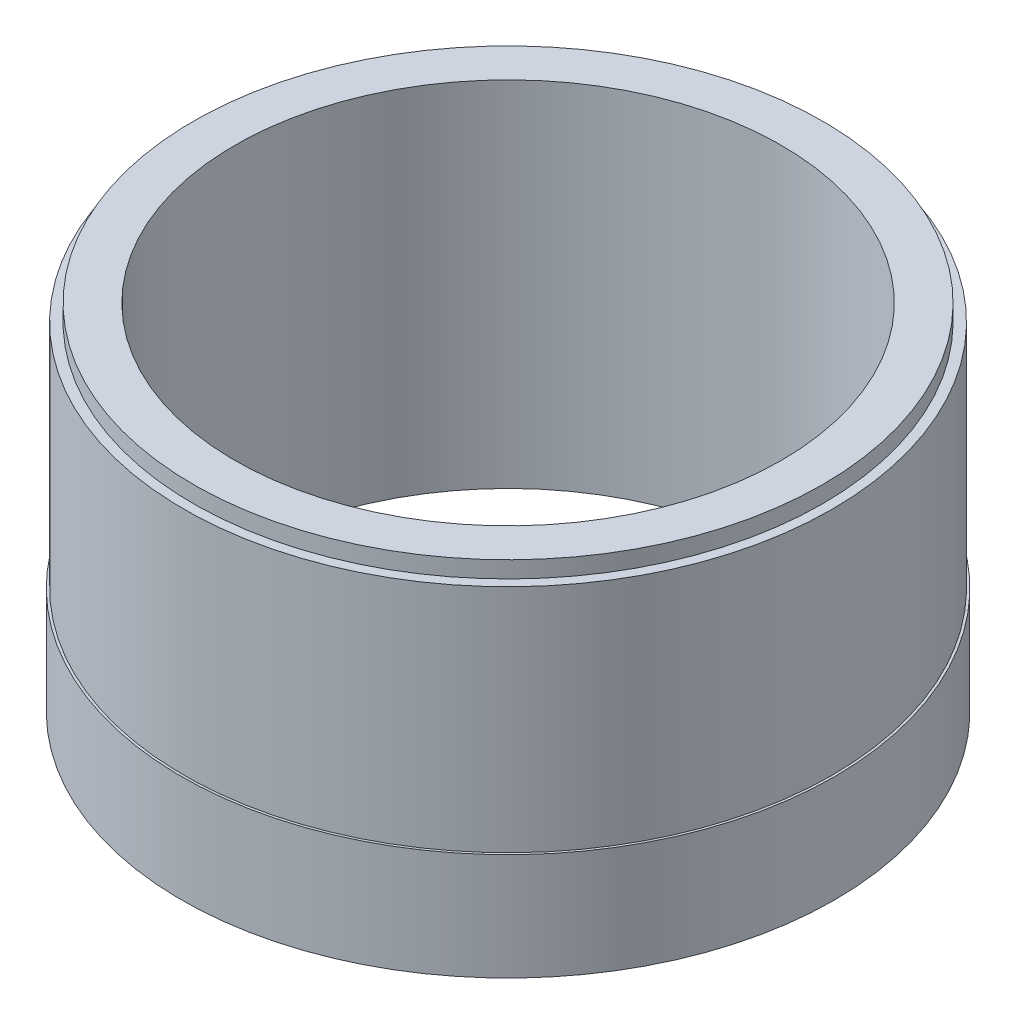
SolidWorks part; units mm, degrees
ref_plane "前基準面" through (0, 0, 0) normal (0, 0, 1) x (1, 0, 0)
ref_plane "上基準面" through (0, 0, 0) normal (0, 1, 0) x (1, 0, 0)
ref_plane "右基準面" through (0, 0, 0) normal (1, 0, 0) x (0, 0, -1)
sketch "草圖1" plane through (0, 0, 0) normal (0, 0, 1) x (1, 0, 0)
  line L0 (136.5, 50) -> (136.5, 147)
  line L1 (136.5, 147) -> (132.5, 147)
  line L2 (132.5, 147) -> (132.5, 154)
  line L3 (132.5, 154) -> (115, 154)
  line L4 (115, 154) -> (115, 5)
  line L5 (115, 5) -> (137.5, 5)
  line L6 (137.5, 5) -> (137.5, 50)
  line L7 (137.5, 50) -> (136.5, 50)
  line L8 (0, 154) -> (0, 5) construction
revolve "旋轉1" add sketch "草圖1" angle 360 about L8
